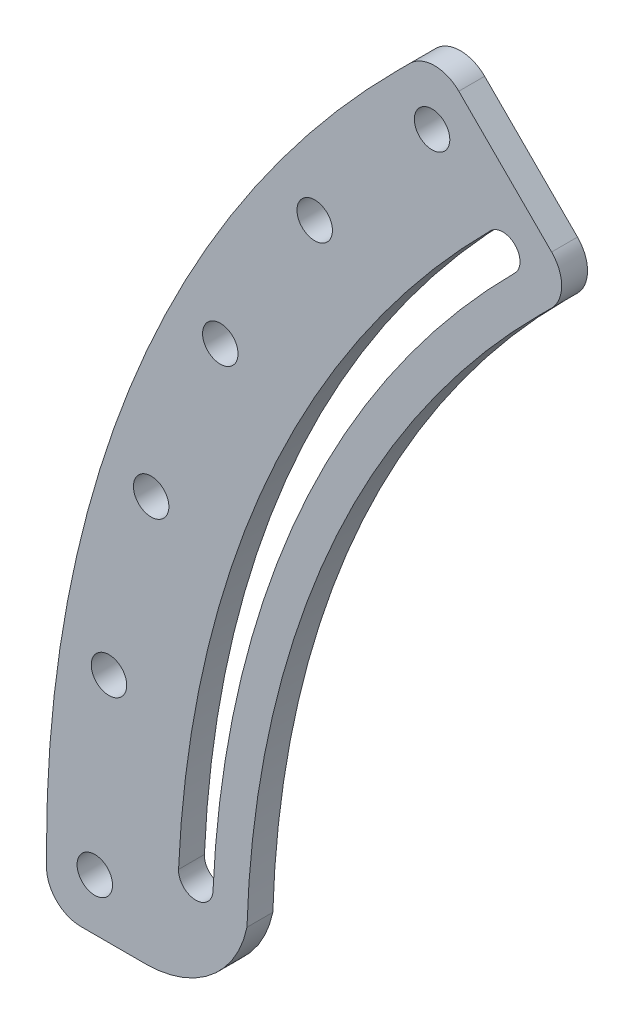
SolidWorks part; units mm, degrees
material "6061 Alloy"
ref_plane "Front Plane" through (0, 0, 0) normal (0, 0, 1) x (1, 0, 0)
ref_plane "Top Plane" through (0, 0, 0) normal (0, 1, 0) x (1, 0, 0)
ref_plane "Right Plane" through (0, 0, 0) normal (1, 0, 0) x (0, 0, -1)
sketch "Sketch1" plane through (0, 0, 0) normal (0, 0, 1) x (1, 0, 0)
  line L0 (-220.98, 0) -> (-184.15, 0) construction
  line L1 (-156.2565, 156.2565) -> (-130.2137, 130.2137) construction
  line L2 (-156.2565, 156.2565) -> (-174.217, 138.2959) construction
  line L3 (-220.98, 0) -> (-220.98, -3.2004)
  line L4 (-214.6554, -9.525) -> (-190.4746, -9.525)
  line L5 (-184.15, -3.2004) -> (-184.15, 0)
  line L6 (-156.2565, 156.2565) -> (-153.9934, 158.5195)
  line L7 (-130.2137, 130.2137) -> (-127.9507, 132.4767)
  line L8 (-127.9507, 141.4211) -> (-145.0491, 158.5195)
  line L9 (-196.6626, 8.5865) -> (-190.3187, 8.3095) construction
  line L10 (-134.7038, 134.7038) -> (-139.194, 139.194) construction
  circle A0 centre (0, 0) radius 184.15 construction
  arc A1 (-130.2137, 130.2137) -> (-184.15, 0) centre (0, 0) ccw
  arc A2 (-220.98, 0) -> (-156.2565, 156.2565) centre (0, 0) cw
  circle A6 centre (-212.09, 0) radius 3.2639
  circle A7 centre (-209.4788, 33.1782) radius 3.2639
  circle A8 centre (-201.7096, 65.5394) radius 3.2639
  circle A9 centre (-188.9736, 96.2868) radius 3.2639
  circle A10 centre (-171.5844, 124.6634) radius 3.2639
  circle A11 centre (-149.9703, 149.9703) radius 3.2639
  arc A13 (-220.98, -3.2004) -> (-214.6554, -9.525) centre (-214.6554, -3.2004) ccw
  arc A14 (-184.15, -3.2004) -> (-190.4746, -9.525) centre (-190.4746, -3.2004) cw
  arc A15 (-145.0491, 158.5195) -> (-153.9934, 158.5195) centre (-149.5213, 154.0473) ccw
  arc A16 (-127.9507, 141.4211) -> (-127.9507, 132.4767) centre (-132.4229, 136.9489) cw
  arc A17 (-190.3187, 8.3095) -> (-134.7038, 134.7038) centre (0, 0) cw
  arc A18 (-196.6626, 8.5865) -> (-139.194, 139.194) centre (0, 0) cw
  arc A19 (-196.6626, 8.5865) -> (-190.3187, 8.3095) centre (-193.4907, 8.448) ccw
  arc A20 (-134.7038, 134.7038) -> (-139.194, 139.194) centre (-136.9489, 136.9489) ccw
  point P26 (-220.98, -9.525)
  point P33 (-149.5213, 162.9916)
  dimension "D1" = 368.3
  dimension "D5" = 6.5278
  dimension "D9" = 6.3246
  dimension "D11" = 6.3246
  dimension "D12" = 6.35
  dimension "D13" = 190.5
  dimension "D14" = 2.5
  dimension "D2" = 45
  dimension "D3" = 36.83
  dimension "D4" = 27.94
  dimension "D7" = 9
  dimension "D8" = 9.525
  dimension "D10" = 9.525
  dimension "D6" = 6
extrude "Boss-Extrude1" add sketch "Sketch1" along normal blind 4.7625
sketch "Sketch2" plane through (0, 0, 0) normal (0, 0, 1) x (1, 0, 0)
  line L0 (-214.6554, -9.525) -> (-190.4746, -9.525) construction
  line L1 (-202.7174, -9.525) -> (-183.6674, -9.525)
  line L3 (-183.6674, -9.525) -> (-183.6674, 9.525)
  line L4 (-202.7174, 9.525) -> (-202.7174, -9.525) construction
  line L5 (-202.7174, 9.525) -> (-183.6674, 9.525) construction
  arc A2 (-202.7174, -9.525) -> (-183.6674, 9.525) centre (-202.7174, 9.525) ccw
  dimension "D1" = 38.1
  dimension "D2" = 11.938
extrude "Cut-Extrude4" cut sketch "Sketch2" along normal through all
